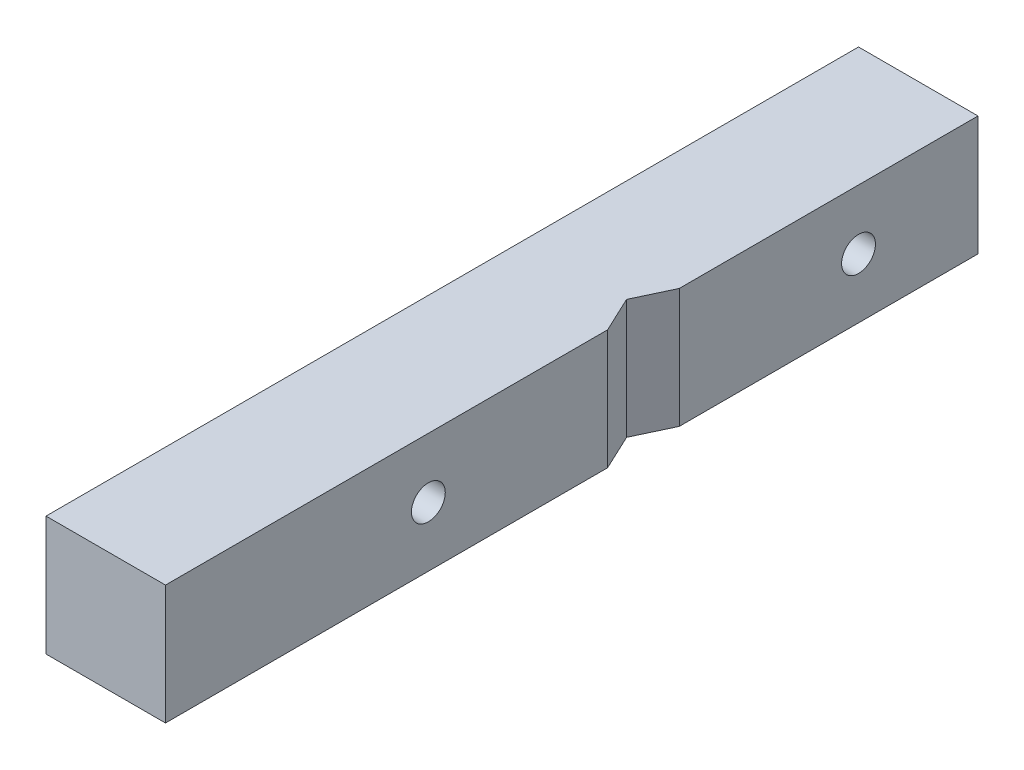
SolidWorks part; units mm, degrees
ref_plane "Front Plane" through (0, 0, 0) normal (0, 0, 1) x (1, 0, 0)
ref_plane "Top Plane" through (0, 0, 0) normal (0, 1, 0) x (1, 0, 0)
ref_plane "Right Plane" through (0, 0, 0) normal (1, 0, 0) x (0, 0, -1)
sketch "Sketch1" plane through (0, 0, 0) normal (0, 0, 1) x (1, 0, 0)
  line L1 (7.9375, -7.9375) -> (-7.9375, -7.9375)
  line L2 (7.9375, -7.9375) -> (7.9375, 7.9375)
  line L3 (7.9375, 7.9375) -> (-7.9375, 7.9375)
  line L4 (-7.9375, -7.9375) -> (-7.9375, 7.9375)
  line L5 (7.9375, -7.9375) -> (-7.9375, 7.9375) construction
  line L6 (7.9375, 7.9375) -> (-7.9375, -7.9375) construction
  point P0 (0, 0)
  dimension "D1" = 15.875
  dimension "D2" = 15.875
extrude "Boss-Extrude1" add sketch "Sketch1" along normal mid plane 107.95
sketch "Sketch2" plane through (0, 7.9375, 0) normal (0, 1, 0) x (1, 0, 0)
  line L0 (7.9375, 14.2875) -> (5.6999, 9.525)
  line L1 (7.9375, -53.975) -> (7.9375, 53.975) construction
  line L2 (5.6999, 9.525) -> (7.9375, 4.7625)
  line L3 (7.9375, -53.975) -> (-7.9375, -53.975) construction
  point P6 (5.6999, 0)
  dimension "D1" = 9.525
  dimension "D2" = 63.5
extrude "Cut-Extrude1" cut sketch "Sketch2" against normal through all and the other way through all
hole_wizard "#12-24 Tapped Hole1" positions "Sketch5" profile "Sketch4" tap size "#12-24" standard "ANSI Inch" end condition through all
sketch "Sketch5" plane through (7.9375, 0, 0) normal (1, 0, 0) x (0, 0, -1)
  line L1 (-53.975, -7.9375) -> (-53.975, 7.9375) construction
  point P0 (38.1, 0)
  point P5 (-19.05, 0)
  dimension "D1" = 57.15
  dimension "D2" = 34.925
sketch "Sketch4" plane through (7.9375, 0, -38.1) normal (0, 1, 0) x (0, 0, -1)
  line L0 (0, 0) -> (0, 15.875)
  line L1 (0, 15.875) -> (2.2479, 15.875)
  line L2 (2.2479, 15.875) -> (2.2479, 0)
  line L5 (2.2479, 0) -> (0, 0)
  line L11 (0, -6.35) -> (0, 107.95) construction
  dimension "Thru Tap Drill Dia." = 4.4958
  dimension "Thru Tap Drill Depth" = 15.875
cosmetic thread "Hole Thread1" parameters "D2"=5.4864
cosmetic thread "Hole Thread2" parameters "D2"=5.4864
